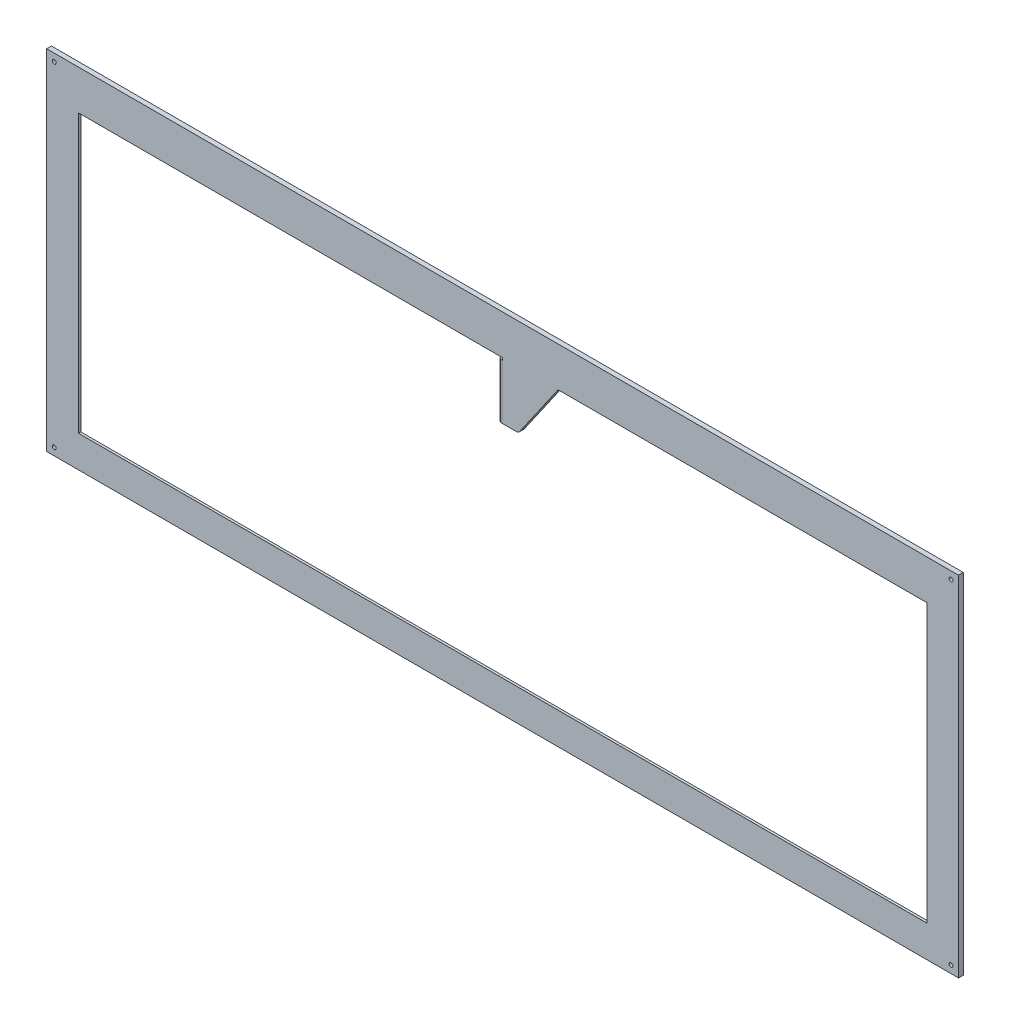
SolidWorks part; units mm, degrees
ref_plane "Front Plane" through (0, 0, 0) normal (0, 0, 1) x (1, 0, 0)
ref_plane "Top Plane" through (0, 0, 0) normal (0, 1, 0) x (1, 0, 0)
ref_plane "Right Plane" through (0, 0, 0) normal (1, 0, 0) x (0, 0, -1)
sketch "Sketch1" plane through (0, 0, 0) normal (0, 0, 1) x (1, 0, 0)
  line L0 (-575, 225) -> (-575, -215)
  line L1 (-535, 175) -> (535, 175)
  line L2 (-535, 175) -> (-535, -175)
  line L3 (-535, -175) -> (535, -175)
  line L4 (535, 175) -> (535, -175)
  line L5 (-535, 175) -> (535, -175) construction
  line L6 (-535, -175) -> (535, 175) construction
  line L7 (-575, -215) -> (575, -215)
  line L8 (575, 225) -> (575, -215)
  line L9 (-575, 225) -> (575, 225)
  line L12 (575, 175) -> (575, -215) construction
  line L13 (-535, 225) -> (535, 225) construction
  line L14 (-575, 175) -> (-575, -215) construction
  point P0 (0, 0)
  dimension "D1" = 350
  dimension "D2" = 1070
  dimension "D3" = 40
  dimension "D4" = 50
extrude "Boss-Extrude1" add sketch "Sketch1" along normal blind 6
sketch "Sketch3" plane through (0, 0, 0) normal (0, 0, -1) x (-1, 0, 0)
  line L0 (-575, 225) -> (575, 225) construction
  line L1 (-575, -215) -> (-575, 225) construction
  line L2 (575, -215) -> (-575, -215) construction
  line L3 (575, 225) -> (575, -215) construction
  circle A0 centre (-565.5, 215.5) radius 2.5
  circle A1 centre (565.5, 215.5) radius 2.5
  circle A2 centre (565.5, -205.5) radius 2.5
  circle A3 centre (-565.5, -205.5) radius 2.5
  dimension "D1" = 5
  dimension "D2" = 9.5
  dimension "D3" = 9.5
  dimension "D4" = 9.5
  dimension "D5" = 9.5
extrude "Cut-Extrude2" cut sketch "Sketch3" against normal through all
sketch "Sketch2" plane through (0, 0, 0) normal (0, 0, -1) x (-1, 0, 0)
  line L0 (-535, 175) -> (535, 175) construction
  line L1 (-535, -175) -> (-535, 175) construction
  line L2 (535, -175) -> (-535, -175) construction
  line L3 (535, 175) -> (535, -175) construction
  line L4 (-535, 175) -> (535, 175)
  line L5 (-535, -175) -> (-535, 175)
  line L6 (535, -175) -> (-535, -175)
  line L7 (535, 175) -> (535, -175)
  line L8 (556, 206) -> (556, -196)
  line L9 (556, -196) -> (-556, -196)
  line L10 (-556, -196) -> (-556, 206)
  line L11 (-556, 206) -> (556, 206)
  line L12 (-535, 206) -> (535, 206) construction
  line L13 (-556, -196) -> (-556, 175) construction
  line L14 (556, 175) -> (556, -196) construction
  line L16 (-575, -215) -> (575, -215)
  line L17 (575, -215) -> (575, 225)
  line L18 (575, 225) -> (-575, 225)
  line L19 (-575, 225) -> (-575, -215)
  line L20 (-575, -215) -> (575, -215) construction
  line L21 (575, -215) -> (575, 225) construction
  line L22 (575, 225) -> (-575, 225) construction
  line L23 (-575, 225) -> (-575, -215) construction
  dimension "D1" = 21
  dimension "D2" = 31
  dimension "D3" = 0
extrude "Cut-Extrude1" cut sketch "Sketch2" against normal blind 3
sketch "Sketch4" plane through (0, 0, 6) normal (0, 0, 1) x (1, 0, 0)
  line L0 (0, 175) -> (0, 103)
  line L1 (535, 175) -> (-535, 175) construction
  line L2 (0, 103) -> (20, 103)
  line L3 (20, 103) -> (70, 175)
  line L4 (-575, -215) -> (575, -215)
  line L5 (575, -215) -> (575, 225)
  line L6 (575, 225) -> (-575, 225)
  line L7 (-575, 225) -> (-575, -215)
  line L8 (-575, -215) -> (575, -215) construction
  line L9 (575, -215) -> (575, 225) construction
  line L10 (575, 225) -> (-575, 225) construction
  line L11 (-575, 225) -> (-575, -215) construction
  line L12 (70, 175) -> (0, 175)
  dimension "D2" = 72
  dimension "D3" = 20
  dimension "D4" = 70
  dimension "D1" = 0
extrude "Boss-Extrude2" add sketch "Sketch4" against normal blind 6
sketch "Sketch5" plane through (0, 0, 6) normal (0, 0, 1) x (1, 0, 0)
  line L0 (0, 103) -> (-6, 103)
  line L1 (-6, 103) -> (-6, 172)
  line L2 (-6, 172) -> (0, 172)
  line L3 (0, 175) -> (0, 103) construction
  line L4 (0, 172) -> (0, 103)
  line L5 (0, 175) -> (-535, 175) construction
  dimension "D1" = 3
  dimension "D2" = 6
extrude "Boss-Extrude3" add sketch "Sketch5" against normal blind 26
sketch "Sketch6" plane through (0, 0, 0) normal (1, 0, 0) x (0, 0, -1)
  line L0 (10, 162) -> (10, 113) construction
  line L1 (13, 162) -> (13, 113)
  line L2 (7, 162) -> (7, 113)
  line L3 (20, 172) -> (0, 172) construction
  line L4 (20, 103) -> (0, 103) construction
  line L5 (20, 103) -> (20, 172) construction
  arc A2 (13, 162) -> (7, 162) centre (10, 162) ccw
  arc A3 (7, 113) -> (13, 113) centre (10, 113) ccw
  point P1 (10, 172)
  point P4 (10, 137.5)
  dimension "D2" = 10
  dimension "D1" = 10
  dimension "D3" = 6
  dimension "D4" = 10
extrude "Cut-Extrude3" cut sketch "Sketch6" against normal blind 26
fillet "Fillet1" radius 5 4 edges at (20, 103, 3) (-6, 137.5, 6) (-3, 103, -20) (-3, 172, -20)
